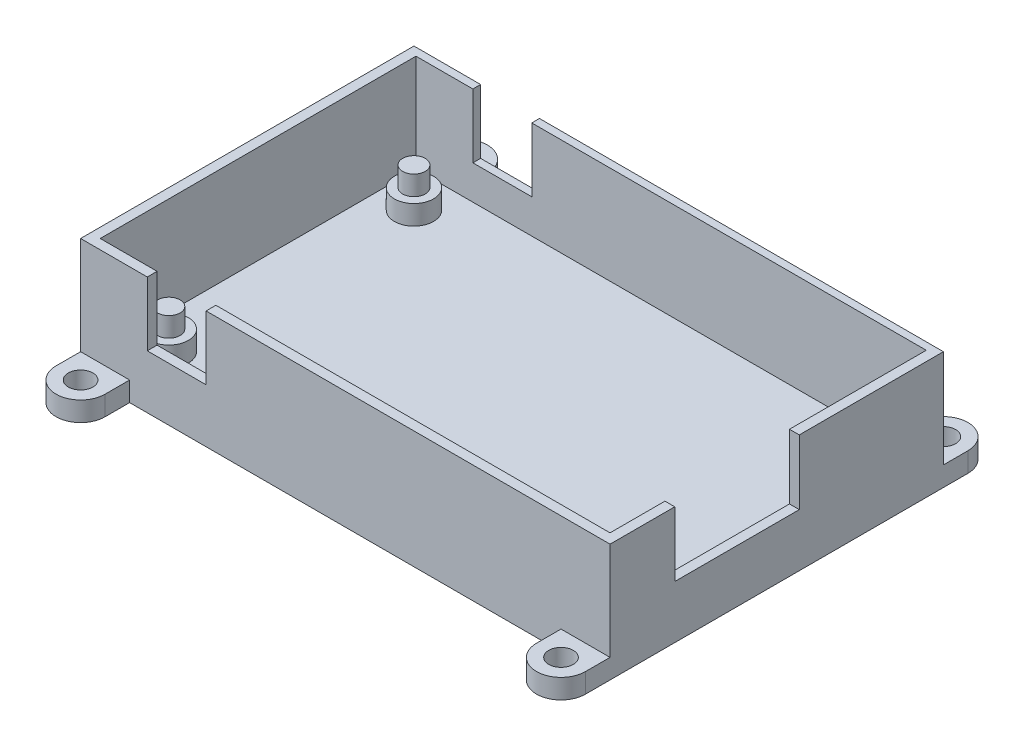
SolidWorks part; units mm, degrees
ref_plane "Front Plane" through (0, 0, 0) normal (0, 0, 1) x (1, 0, 0)
ref_plane "Top Plane" through (0, 0, 0) normal (0, 1, 0) x (1, 0, 0)
ref_plane "Right Plane" through (0, 0, 0) normal (1, 0, 0) x (0, 0, -1)
sketch "Sketch1" plane through (0, 0, 0) normal (0, 1, 0) x (1, 0, 0)
  line L1 (0, 0) -> (68.58, 0)
  line L2 (0, 0) -> (0, 43.18)
  line L3 (0, 43.18) -> (68.58, 43.18)
  line L4 (68.58, 0) -> (68.58, 43.18)
  point P13 (34.29, 43.18)
  point P14 (0, 21.59)
  dimension "D1" = 43.18
  dimension "D2" = 68.58
extrude "Boss-Extrude1" add sketch "Sketch1" along normal blind 2.54
sketch "Sketch5" plane through (0, 2.54, 0) normal (0, 1, 0) x (1, 0, 0)
  line L0 (68.58, 43.18) -> (0, 43.18) construction
  line L1 (68.58, 43.18) -> (0, 43.18) construction
  line L2 (0, 43.18) -> (0, 0) construction
  circle A0 centre (5.715, 37.465) radius 2.54
  circle A1 centre (62.865, 37.465) radius 2.54
  circle A2 centre (5.715, 5.715) radius 2.54
  circle A3 centre (62.865, 5.715) radius 2.54
  point P8 (34.29, 43.18)
  point P11 (34.29, 43.18)
  point P15 (34.29, 43.18)
  point P16 (34.29, 43.18)
  point P17 (0, 21.59)
  point P20 (0, 21.59)
  point P21 (0, 21.59)
  point P22 (0, 21.59)
  dimension "D1" = 5.08
  dimension "D2" = 5.08
  dimension "D3" = 5.08
  dimension "D4" = 5.08
  dimension "D5" = 28.575
  dimension "D6" = 28.575
  dimension "D7" = 28.575
  dimension "D8" = 15.875
  dimension "D9" = 28.575
  dimension "D10" = 15.875
  dimension "D11" = 15.875
  dimension "D12" = 15.875
extrude "Boss-Extrude2" add sketch "Sketch5" along normal blind 2.54
sketch "Sketch6" plane through (0, 2.54, 0) normal (0, 1, 0) x (1, 0, 0)
  line L0 (0, 43.18) -> (0, 0)
  line L1 (0, 0) -> (68.58, 0)
  line L2 (68.58, 0) -> (68.58, 43.18)
  line L3 (68.58, 43.18) -> (0, 43.18)
  line L4 (1.27, 42.1719) -> (1.27, 1.27)
  line L5 (1.27, 1.27) -> (67.31, 1.27)
  line L6 (67.31, 1.27) -> (67.31, 42.2296)
  line L7 (67.31, 42.2296) -> (1.27, 42.1719)
  dimension "D1" = 1.27
  dimension "D2" = 1.27
  dimension "D3" = 1.27
  dimension "D4" = 0.05
extrude "Boss-Extrude3" add sketch "Sketch6" along normal blind 12.7
sketch "Sketch7" plane through (0, 5.08, 0) normal (0, 1, 0) x (1, 0, 0)
  circle A0 centre (5.715, 37.465) radius 1.4605
  circle A1 centre (5.715, 5.715) radius 1.4605
  circle A2 centre (62.865, 5.715) radius 1.4605
  circle A3 centre (62.865, 37.465) radius 1.4605
  dimension "D1" = 2.921
  dimension "D2" = 2.921
  dimension "D3" = 2.921
  dimension "D4" = 2.921
extrude "Boss-Extrude4" add sketch "Sketch7" along normal blind 2.54
sketch "Sketch8" plane through (0, 0, 0) normal (0, 0, 1) x (1, 0, 0)
  line L0 (0, 15.24) -> (68.58, 15.24) construction
  line L1 (8.636, 15.24) -> (16.256, 15.24)
  line L2 (8.636, 15.24) -> (8.636, 6.9544)
  line L3 (8.636, 6.9544) -> (16.256, 6.9544)
  line L4 (16.256, 15.24) -> (16.256, 6.9544)
  line L5 (0, 15.24) -> (0, 0) construction
  dimension "D1" = 8.636
  dimension "D2" = 7.62
  dimension "D3" = 8.2856
extrude "Cut-Extrude1" cut sketch "Sketch8" against normal through all
sketch "Sketch9" plane through (68.58, 0, 0) normal (1, 0, 0) x (0, 0, -1)
  line L0 (0, 15.24) -> (43.18, 15.24) construction
  line L1 (8.382, 15.24) -> (24.511, 15.24)
  line L2 (8.382, 15.24) -> (8.382, 6.858)
  line L3 (8.382, 6.858) -> (24.511, 6.858)
  line L4 (24.511, 15.24) -> (24.511, 6.858)
  line L5 (0, 15.24) -> (0, 0) construction
  dimension "D1" = 24.511
  dimension "D2" = 8.382
  dimension "D3" = 8.382
extrude "Cut-Extrude2" cut sketch "Sketch9" against normal blind 2.032
sketch "Sketch10" plane through (0, 0, 0) normal (0, -1, 0) x (1, 0, 0)
  line L2 (0, 3.175) -> (0, 0)
  line L3 (0, 0) -> (6.35, 0)
  line L4 (6.35, 3.175) -> (6.35, 0)
  line L9 (6.35, -46.355) -> (6.35, -43.18)
  line L10 (0, -43.18) -> (6.35, -43.18)
  line L11 (0, -46.355) -> (0, -43.18)
  line L12 (68.58, -46.355) -> (68.58, -43.18)
  line L13 (68.58, -43.18) -> (62.23, -43.18)
  line L14 (62.23, -46.355) -> (62.23, -43.18)
  line L15 (62.23, 3.175) -> (62.23, 0)
  line L16 (68.58, 0) -> (62.23, 0)
  line L17 (68.58, 3.175) -> (68.58, 0)
  arc A0 (6.35, 3.175) -> (0, 3.175) centre (3.175, 3.175) ccw
  arc A1 (6.35, -46.355) -> (0, -46.355) centre (3.175, -46.355) cw
  arc A2 (62.23, -46.355) -> (68.58, -46.355) centre (65.405, -46.355) ccw
  arc A3 (62.23, 3.175) -> (68.58, 3.175) centre (65.405, 3.175) cw
  dimension "D1" = 6.35
  dimension "D2" = 0
  dimension "D3" = 0
extrude "Boss-Extrude5" add sketch "Sketch10" against normal blind 2.54
hole_wizard "1/8 (0.125) Diameter Hole1" positions "Sketch14" profile "Sketch13" hole size "1/8" standard "ANSI Inch" end condition through all
sketch "Sketch14" plane through (0, 2.54, 0) normal (0, 1, 0) x (1, 0, 0)
  arc A0 (0, -3.175) -> (6.35, -3.175) centre (3.175, -3.175) ccw construction
  arc A1 (62.23, -3.175) -> (68.58, -3.175) centre (65.405, -3.175) ccw construction
  arc A2 (6.35, 46.355) -> (0, 46.355) centre (3.175, 46.355) ccw construction
  arc A5 (68.58, 46.355) -> (62.23, 46.355) centre (65.405, 46.355) ccw construction
  point P0 (65.405, 46.355)
  point P2 (3.175, 46.355)
  point P4 (3.175, -3.175)
  point P6 (65.405, -3.175)
  point P9 (3.175, -6.35)
  point P14 (65.405, -6.35)
  point P20 (3.175, 49.53)
  point P32 (66.2607, 46.3565)
  point P36 (65.405, 49.53)
  dimension "D1" = 3.175
  dimension "D2" = 3.175
  dimension "D3" = 3.175
  dimension "D4" = 3.175
  dimension "D5" = 3.175
  dimension "D6" = 3.175
  dimension "D7" = 3.175
  dimension "D8" = 3.175
sketch "Sketch13" plane through (65.405, 2.54, -46.355) normal (1, 0, 0) x (0, 0, 1)
  line L0 (0, 0) -> (0, 2.5401)
  line L1 (0, 2.5401) -> (1.5875, 2.5401)
  line L2 (1.5875, 2.5401) -> (1.5875, 0)
  line L5 (1.5875, 0) -> (0, 0)
  line L11 (0, -6.35) -> (0, 107.95) construction
  dimension "Thru Hole Dia." = 3.175
  dimension "Thru Hole Depth" = 2.5401
